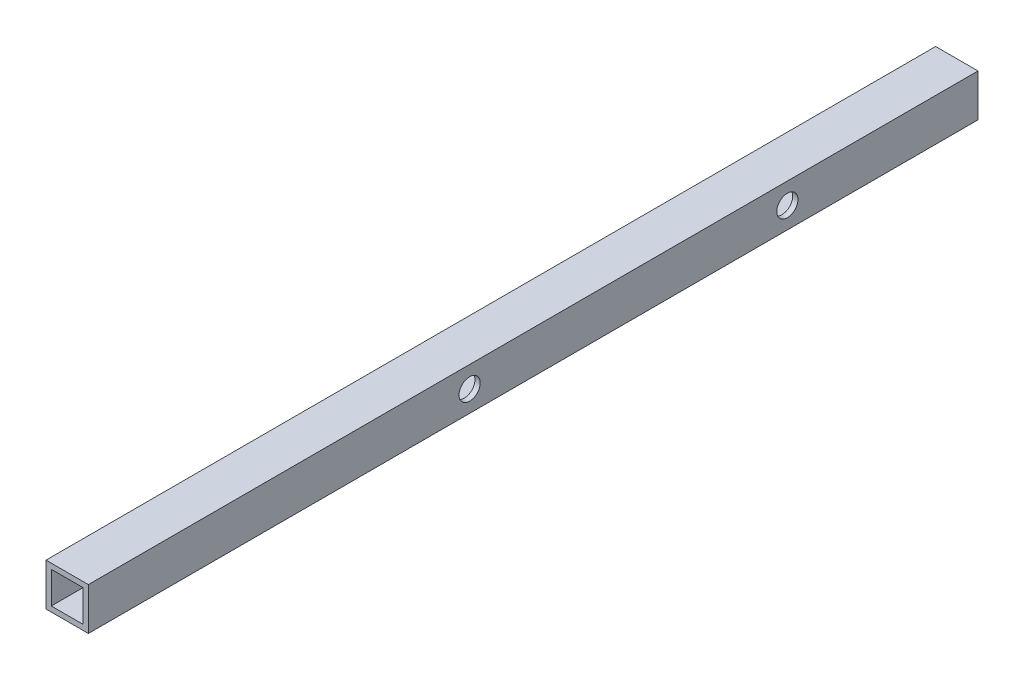
SolidWorks part; units mm, degrees
material "1060 Alloy"
ref_plane "Front Plane" through (0, 0, 0) normal (0, 0, 1) x (1, 0, 0)
ref_plane "Top Plane" through (0, 0, 0) normal (0, 1, 0) x (1, 0, 0)
ref_plane "Right Plane" through (0, 0, 0) normal (1, 0, 0) x (0, 0, -1)
sketch "Sketch1" plane through (0, 0, 0) normal (0, 0, 1) x (1, 0, 0)
  line L1 (-12.7, -12.7) -> (12.7, -12.7)
  line L2 (-12.7, -12.7) -> (-12.7, 12.7)
  line L3 (-12.7, 12.7) -> (12.7, 12.7)
  line L4 (12.7, -12.7) -> (12.7, 12.7)
  line L5 (-12.7, -12.7) -> (12.7, 12.7) construction
  line L6 (-12.7, 12.7) -> (12.7, -12.7) construction
  point P0 (0, 0)
  dimension "D1" = 25.4
extrude "Extrude-Thin1" add sketch "Sketch1" along normal blind 533.4 thin thin type one direction reverse wall 3.175
sketch "Sketch2" plane through (12.7, 0, 0) normal (1, 0, 0) x (0, 0, -1)
  line L0 (0, -12.7) -> (0, 12.7) construction
  line L1 (-533.4, -12.7) -> (-533.4, 12.7) construction
  circle A0 centre (-304.8, 0) radius 6.35
  circle A1 centre (-114.3, 0) radius 6.35
  dimension "D1" = 12.7
  dimension "D2" = 114.3
  dimension "D3" = 228.6
extrude "Cut-Extrude1" cut sketch "Sketch2" against normal through all
